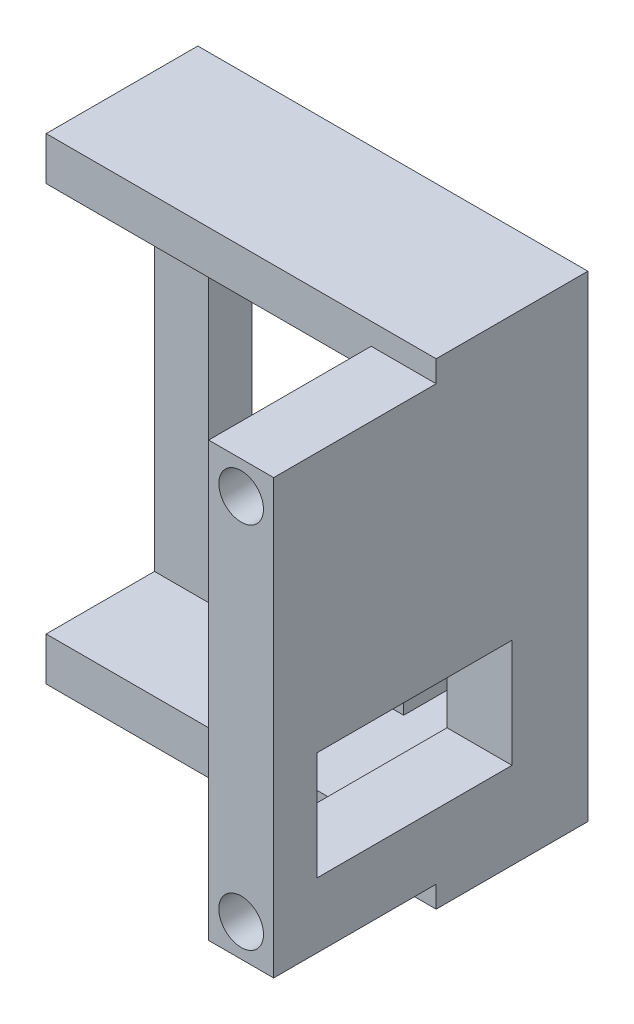
SolidWorks part; units mm, degrees
ref_plane "Front Plane" through (0, 0, 0) normal (1, 0, 0) x (0, 1, 0)
ref_plane "Top Plane" through (0, 0, 0) normal (0, 0, 1) x (0, 1, 0)
ref_plane "Right Plane" through (0, 0, 0) normal (0, 1, 0) x (-1, 0, 0)
sketch "Sketch1" plane through (0, 0, 0) normal (0, 0, 1) x (0, 1, 0)
  line L0 (4.5125, -3.675) -> (4.5125, 2.325) construction
  line L1 (-15.4875, 2.325) -> (24.5125, 2.325)
  line L2 (-15.4875, 2.325) -> (-15.4875, -3.675)
  line L3 (-15.4875, -3.675) -> (24.5125, -3.675)
  line L4 (24.5125, 2.325) -> (24.5125, -3.675)
  circle A0 centre (-12.4875, -0.675) radius 2.06
  circle A2 centre (21.5125, -0.675) radius 2.06
  dimension "D5" = 4.12
  dimension "D1" = 3
  dimension "D2" = 40
  dimension "D3" = 6
  dimension "D4" = 3
extrude "Boss-Extrude1" add sketch "Sketch1" along normal blind 25 contours L1 L4 L3 L2
sketch "Sketch2" plane through (0, 0, 0) normal (0, 0, -1) x (1, 0, 0)
  line L0 (3.675, -4.5125) -> (-34.5695, -4.5125) construction
  line L1 (3.675, 15.4875) -> (-2.325, 15.4875)
  line L2 (3.675, 15.4875) -> (3.675, -24.5125)
  line L3 (3.675, -24.5125) -> (-2.325, -24.5125)
  line L4 (-2.325, 15.4875) -> (-2.325, -24.5125)
  line L6 (-2.325, 15.4875) -> (-2.325, 11.4875)
  line L13 (3.675, 13.4875) -> (-32.325, 13.4875)
  line L14 (3.675, 13.4875) -> (3.675, 17.4875)
  line L15 (3.675, 17.4875) -> (-32.325, 17.4875)
  line L16 (-32.325, 13.4875) -> (-32.325, 17.4875)
  line L17 (-32.325, -22.5125) -> (-32.325, -26.5125)
  line L18 (3.675, -26.5125) -> (-32.325, -26.5125)
  line L19 (3.675, -22.5125) -> (3.675, -26.5125)
  line L20 (3.675, -22.5125) -> (-32.325, -22.5125)
  line L21 (-2.325, -24.5125) -> (-2.325, -20.5125)
  line L22 (3.675, -24.5125) -> (-2.325, -24.5125)
  dimension "D1" = 2
  dimension "D2" = 4
  dimension "D3" = 36
extrude "Boss-Extrude2" add sketch "Sketch2" against normal blind 10
sketch "Sketch4" plane through (0, 0, 0) normal (0, 0, -1) x (1, 0, 0)
  line L0 (3.675, 17.4875) -> (3.675, -26.5125) construction
  line L1 (-32.325, 17.4875) -> (3.675, 17.4875)
  line L2 (-32.325, 17.4875) -> (-32.325, 13.4875)
  line L3 (-32.325, 13.4875) -> (3.675, 13.4875)
  line L4 (3.675, 17.4875) -> (3.675, 13.4875)
  line L5 (-2.325, -22.5125) -> (-32.325, -22.5125) construction
  line L6 (-32.325, -26.5125) -> (3.675, -26.5125)
  line L7 (-32.325, -26.5125) -> (-32.325, -22.5125)
  line L8 (-32.325, -22.5125) -> (3.675, -22.5125)
  line L9 (3.675, -26.5125) -> (3.675, -22.5125)
  line L10 (-2.325, 13.4875) -> (-32.325, 13.4875) construction
  line L12 (-32.325, 13.4875) -> (-27.325, 13.4875)
  line L13 (-32.325, 13.4875) -> (-32.325, -22.5125)
  line L14 (-32.325, -22.5125) -> (-27.325, -22.5125)
  line L15 (-27.325, 13.4875) -> (-27.325, -22.5125)
  line L16 (-14.325, 13.4875) -> (-9.325, 13.4875)
  line L17 (-14.325, 13.4875) -> (-14.325, -22.5125)
  line L18 (-14.325, -22.5125) -> (-9.325, -22.5125)
  line L19 (-9.325, 13.4875) -> (-9.325, -22.5125)
  line L20 (-2.325, 13.4875) -> (3.675, 13.4875)
  line L21 (-2.325, 13.4875) -> (-2.325, -22.5125)
  line L22 (-2.325, -22.5125) -> (3.675, -22.5125)
  line L23 (3.675, 13.4875) -> (3.675, -22.5125)
  line M7 (3.675, -26.5125) -> (3.675, 17.4875)
  line M8 (3.675, 17.4875) -> (-32.325, 17.4875)
  line M9 (-32.325, 17.4875) -> (-32.325, 13.4875)
  line M10 (-32.325, 13.4875) -> (-2.325, 13.4875)
  line M11 (-2.325, 13.4875) -> (-2.325, -22.5125)
  line M12 (-2.325, -22.5125) -> (-32.325, -22.5125)
  line M13 (-32.325, -22.5125) -> (-32.325, -26.5125)
  line M14 (-32.325, -26.5125) -> (3.675, -26.5125)
  circle M15 centre (0.675, 12.4875) radius 2.06
  circle M16 centre (0.675, -21.5125) radius 2.06
  dimension "D1" = 5
  dimension "D2" = 5
extrude "Boss-Extrude4" add sketch "Sketch4" along normal blind 4 contours L3 M10 M15 M7 M8 M9 | L3 M15 | L3 M15 | L8 L3 M11 M16 M7 M15 | L8 M16 | L8 M16 | L8 M12 M13 M14 M7 M16 | L15 L13 L8 M10 | L17 L18 L19 L16
sketch "Sketch5" plane through (-2.325, 0, 0) normal (-1, 0, 0) x (0, -1, 0)
  line L0 (13.4875, 10) -> (13.4875, 0) construction
  line L1 (-0.5125, 21) -> (9.4875, 21)
  line L2 (-0.5125, 21) -> (-0.5125, 3)
  line L3 (-0.5125, 3) -> (9.4875, 3)
  line L4 (9.4875, 21) -> (9.4875, 3)
  line L5 (13.4875, 0) -> (-22.5125, 0) construction
  dimension "D1" = 18
  dimension "D2" = 10
  dimension "D3" = 4
  dimension "D4" = 3
extrude "Cut-Extrude1" cut sketch "Sketch5" against normal blind 8
